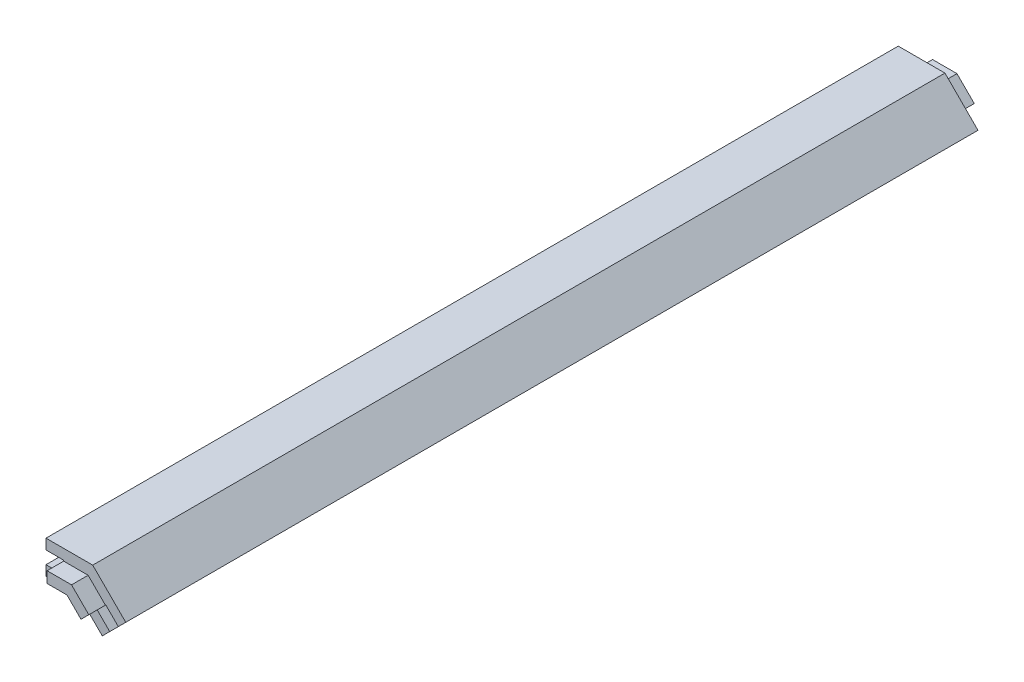
SolidWorks part; units mm, degrees
material "Custom Plastic"
ref_plane "Front Plane" through (0, 0, 0) normal (0, 0, 1) x (1, 0, 0)
ref_plane "Top Plane" through (0, 0, 0) normal (0, 1, 0) x (1, 0, 0)
ref_plane "Right Plane" through (0, 0, 0) normal (1, 0, 0) x (0, 0, -1)
sketch "Sketch1" plane through (0, 0, 0) normal (0, 0, 1) x (1, 0, 0)
  line L0 (0, 0) -> (10, 0)
  line L1 (10, 0) -> (17.0711, -7.0711)
  line L2 (0, -2.5) -> (8.9645, -2.5)
  line L3 (8.9645, -2.5) -> (15.3033, -8.8388)
  line L4 (0, 2.5) -> (11.0355, 2.5)
  line L5 (11.0355, 2.5) -> (18.8388, -5.3033)
  line L6 (0, 2.5) -> (0, -2.5)
  line L7 (15.3033, -8.8388) -> (18.8388, -5.3033)
  dimension "D1" = 10
  dimension "D2" = 10
  dimension "D3" = 135
  dimension "D4" = 2.5
  dimension "D5" = 2.5
extrude "Boss-Extrude1" add sketch "Sketch1" along normal blind 7.5 contours L7 L5 L4 L6 L2 L3
sketch "Sketch2" plane through (0, 0, 7.5) normal (0, 0, 1) x (1, 0, 0)
  line L0 (8.9645, -2.5) -> (15.3033, -8.8388) construction
  line L1 (11.0355, 2.5) -> (18.8388, -5.3033) construction
  line L2 (15.3033, -8.8388) -> (18.8388, -5.3033) construction
  line L3 (0, -2.5) -> (8.9645, -2.5) construction
  line L4 (0, 2.5) -> (0, -2.5) construction
  line L5 (15.3033, -8.8388) -> (18.8388, -5.3033) construction
  line L6 (15.1265, -9.0156) -> (20.7834, -14.6725)
  line L7 (-8, 2.875) -> (0, 2.875)
  line L9 (-8, -2.875) -> (0, -2.875)
  line L10 (0, 2.875) -> (0, -2.875)
  line L11 (-8, -2.875) -> (-8, -7.5)
  line L12 (24.6725, -10.7834) -> (19.0156, -5.1265)
  line L13 (24.6725, -10.7834) -> (28.0312, -7.4246)
  line L14 (15.1265, -9.0156) -> (19.0156, -5.1265)
  line L15 (0, 2.5) -> (11.0355, 2.5) construction
  line L18 (6.8934, -7.5) -> (17.4246, -18.0312)
  line L19 (17.4246, -18.0312) -> (20.7834, -14.6725)
  line L20 (28.0312, -7.4246) -> (13.1066, 7.5)
  line L21 (13.1066, 7.5) -> (-8, 7.5)
  line L22 (-8, 7.5) -> (-8, 2.875)
  line L23 (-8, -7.5) -> (6.8934, -7.5)
  point P0 (0, 0)
  point P26 (17.0711, -7.0711)
  point P28 (17.0711, -7.0711)
  dimension "D1" = 5.5
  dimension "D2" = 5
  dimension "D3" = 21.1066
  dimension "D5" = 8
  dimension "D6" = 8
  dimension "D7" = 5.75
  dimension "D9" = 5
  dimension "D10" = 5
  dimension "D11" = 5.5
  dimension "D12" = 90
extrude "Boss-Extrude2" add sketch "Sketch2" along normal blind 385
sketch "Sketch4" plane through (0, 0, 392.5) normal (0, 0, 1) x (1, 0, 0)
  line L6 (15.1265, -9.0156) -> (19.0156, -5.1265) construction
  line L7 (28.0312, -7.4246) -> (13.1066, 7.5) construction
  line L8 (13.1066, 7.5) -> (-8, 7.5) construction
  line L9 (6.8934, -7.5) -> (17.4246, -18.0312) construction
  line L10 (-8, -7.5) -> (6.8934, -7.5) construction
  line L17 (15.3033, -8.8388) -> (18.8388, -5.3033)
  line L18 (0, -2.5) -> (8.9645, -2.5)
  line L19 (8.9645, -2.5) -> (15.3033, -8.8388)
  line L21 (18.8388, -5.3033) -> (11.0355, 2.5)
  line L22 (11.0355, 2.5) -> (0, 2.5)
  line L33 (0, 2.5) -> (0, -2.5)
  dimension "D1" = 0
  dimension "D2" = 0
  dimension "D3" = 5
  dimension "D4" = 5
  dimension "D5" = 5
  dimension "D6" = 5
extrude "Boss-Extrude3" add sketch "Sketch4" along normal blind 7.5
